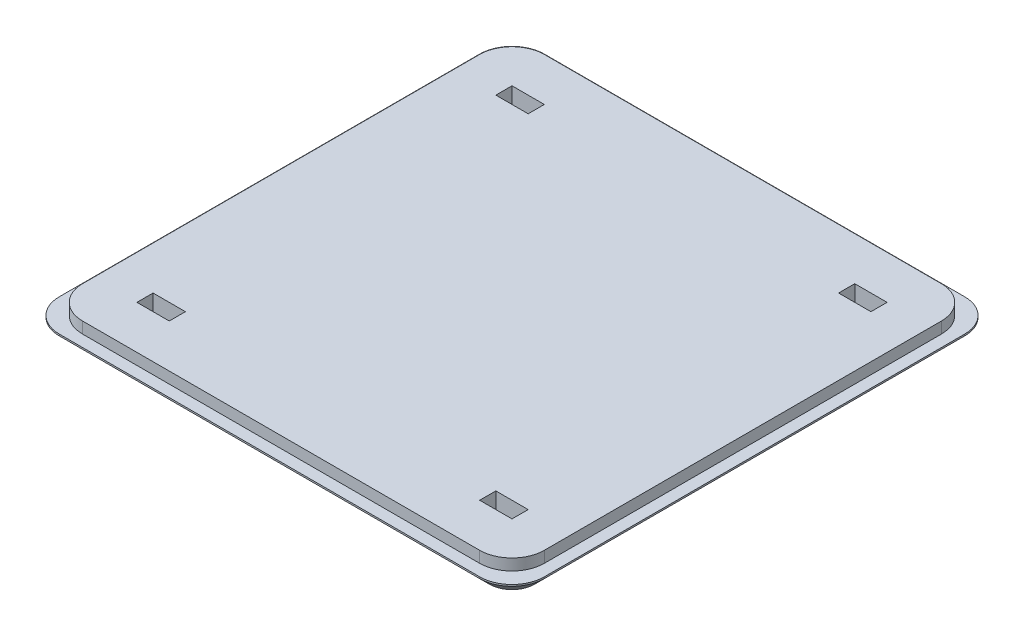
SolidWorks part; units mm, degrees
ref_plane "Front Plane" through (0, 0, 0) normal (0, 0, 1) x (1, 0, 0)
ref_plane "Top Plane" through (0, 0, 0) normal (0, 1, 0) x (1, 0, 0)
ref_plane "Right Plane" through (0, 0, 0) normal (1, 0, 0) x (0, 0, -1)
sketch "Sketch1" plane through (0, 0, 0) normal (0, 1, 0) x (1, 0, 0)
  line L1 (0, 0) -> (150, 0)
  line L2 (0, 0) -> (0, 150)
  line L3 (0, 150) -> (150, 150)
  line L4 (150, 0) -> (150, 150)
  dimension "D1" = 150
  dimension "D2" = 150
extrude "Boss-Extrude1" add sketch "Sketch1" along normal blind 3.5
sketch "Sketch2" plane through (0, 3.5, 0) normal (0, 1, 0) x (1, 0, 0)
  line L0 (150, 150) -> (0, 150) construction
  line L1 (3.6, 146.4) -> (146.4, 146.4)
  line L2 (3.6, 146.4) -> (3.6, 3.6)
  line L3 (3.6, 3.6) -> (146.4, 3.6)
  line L4 (146.4, 146.4) -> (146.4, 3.6)
  line L5 (0, 150) -> (0, 0) construction
  line L6 (150, 0) -> (150, 150) construction
  line L9 (0, 0) -> (150, 0) construction
  dimension "D1" = 3.6
  dimension "D2" = 3.6
  dimension "D3" = 3.6
  dimension "D4" = 3.6
extrude "Boss-Extrude2" add sketch "Sketch2" along normal blind 3.5
fillet "Fillet9" radius 10 2 edges at (146.4, 5.25, -3.6) (150, 1.75, 0)
fillet "Fillet10" radius 10 6 edges at (0, 1.75, -150) (3.6, 5.25, -146.4) (0, 1.75, 0) (3.6, 5.25, -3.6) (146.4, 5.25, -146.4) (150, 1.75, -150)
chamfer "Chamfer3" distance 3 angle 45 8 edges at (150, 0, -75) (147.0711, 0, -147.0711) (75, 0, -150) (2.9289, 0, -147.0711) (147.0711, 0, -2.9289) (0, 0, -75) (2.9289, 0, -2.9289) (75, 0, 0)
sketch "Sketch3" plane through (0, 7, 0) normal (0, 1, 0) x (1, 0, 0)
  line L0 (0, 140) -> (0, 10) construction
  line L1 (17, 22) -> (27, 22)
  line L2 (17, 22) -> (17, 17)
  line L3 (17, 17) -> (27, 17)
  line L4 (27, 22) -> (27, 17)
  line L5 (10, 0) -> (140, 0) construction
  point P4 (17, 19.5)
  dimension "D1" = 10
  dimension "D2" = 5
  dimension "D3" = 17
  dimension "D4" = 17
extrude "Cut-Extrude1" cut sketch "Sketch3" against normal blind 10
sketch "Sketch4" plane through (0, 7, 0) normal (0, 1, 0) x (1, 0, 0)
  line L0 (140, 150) -> (10, 150) construction
  line L1 (17, 128) -> (27, 128)
  line L2 (17, 128) -> (17, 133)
  line L3 (17, 133) -> (27, 133)
  line L4 (27, 128) -> (27, 133)
  line L5 (0, 140) -> (0, 10) construction
  dimension "D1" = 5
  dimension "D2" = 10
  dimension "D3" = 17
  dimension "D4" = 17
extrude "Cut-Extrude2" cut sketch "Sketch4" against normal blind 10
sketch "Sketch5" plane through (0, 7, 0) normal (0, 1, 0) x (1, 0, 0)
  line L0 (10, 0) -> (140, 0) construction
  line L1 (123, 17) -> (133, 17)
  line L2 (123, 17) -> (123, 22)
  line L3 (123, 22) -> (133, 22)
  line L4 (133, 17) -> (133, 22)
  line L5 (150, 10) -> (150, 140) construction
  dimension "D1" = 5
  dimension "D2" = 10
  dimension "D3" = 17
  dimension "D4" = 17
extrude "Cut-Extrude3" cut sketch "Sketch5" against normal blind 10
sketch "Sketch6" plane through (0, 7, 0) normal (0, 1, 0) x (1, 0, 0)
  line L0 (140, 150) -> (10, 150) construction
  line L1 (123, 128) -> (133, 128)
  line L2 (123, 128) -> (123, 133)
  line L3 (123, 133) -> (133, 133)
  line L4 (133, 128) -> (133, 133)
  line L5 (150, 10) -> (150, 140) construction
  dimension "D1" = 5
  dimension "D2" = 10
  dimension "D3" = 17
  dimension "D4" = 17
extrude "Cut-Extrude4" cut sketch "Sketch6" against normal blind 10
